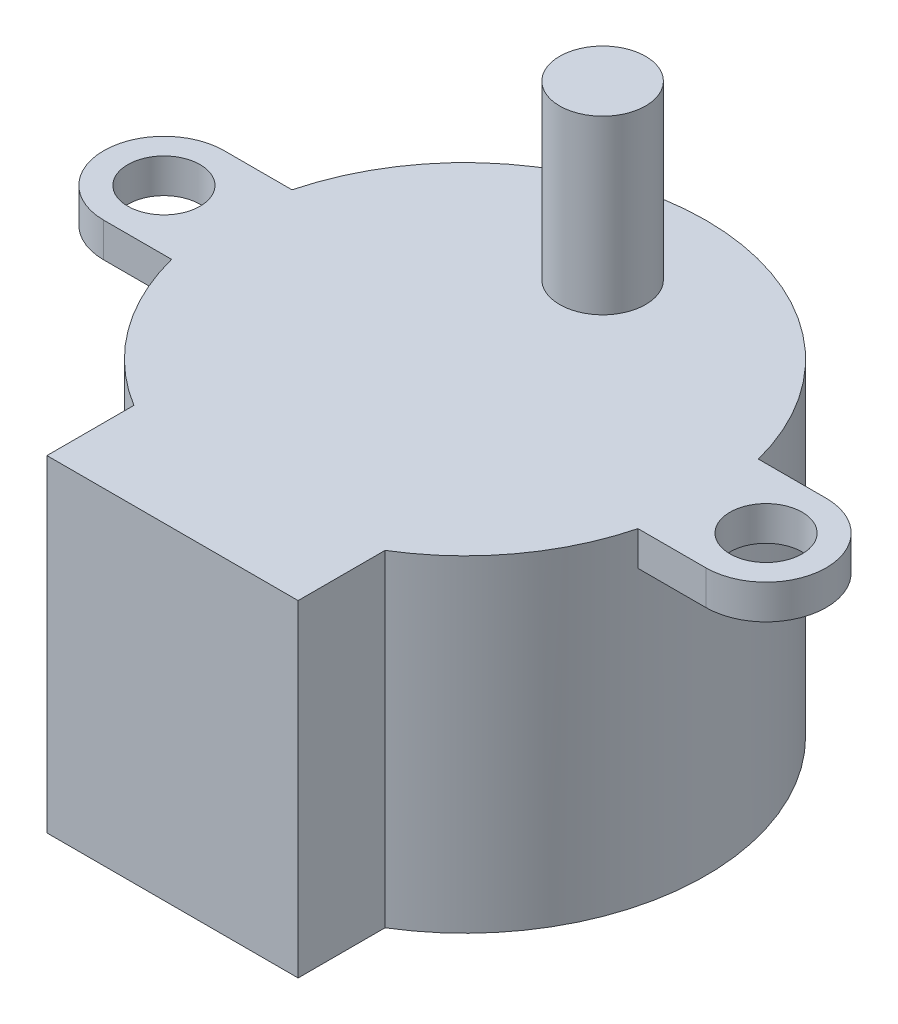
SolidWorks part; units mm, degrees
ref_plane "Спереди" through (0, 0, 0) normal (0, 0, 1) x (1, 0, 0)
ref_plane "Сверху" through (0, 0, 0) normal (0, 1, 0) x (1, 0, 0)
ref_plane "Справа" through (0, 0, 0) normal (1, 0, 0) x (0, 0, -1)
sketch "Sketch1" plane through (0, 0, 0) normal (0, 1, 0) x (1, 0, 0)
  circle A0 centre (0, 0) radius 14
  dimension "D1" = 28
extrude "Boss-Extrude1" add sketch "Sketch1" along normal blind 19
sketch "Sketch2" plane through (0, 19, 0) normal (0, 1, 0) x (1, 0, 0)
  line L0 (-7.3, -17) -> (7.3, -17)
  line L1 (-7.3, -17) -> (-7.3, -11.5042)
  line L2 (-7.3, -11.5042) -> (7.3, -11.5042)
  line L3 (7.3, -11.5042) -> (7.3, -17)
  dimension "D1" = 17
  dimension "D2" = 7.3
  dimension "D3" = 7.3
extrude "Boss-Extrude2" add sketch "Sketch2" against normal blind 19
sketch "Sketch3" plane through (0, 19, 0) normal (0, 1, 0) x (1, 0, 0)
  line L0 (-17.5, 3.5) -> (-12.3999, 3.5)
  line L1 (-12.3999, 3.5) -> (-12.3999, -3.5)
  line L2 (-12.3999, -3.5) -> (-17.5, -3.5)
  line L3 (0, 5.0406) -> (0, -4.2252) construction
  line L4 (12.3999, -3.5) -> (17.5, -3.5)
  line L5 (12.3999, 3.5) -> (12.3999, -3.5)
  line L6 (17.5, 3.5) -> (12.3999, 3.5)
  circle A0 centre (-17.5, 0) radius 2.1
  arc A1 (-17.5, 3.5) -> (-17.5, -3.5) centre (-17.5, 0) ccw
  arc A2 (17.5, 3.5) -> (17.5, -3.5) centre (17.5, 0) cw
  circle A3 centre (17.5, 0) radius 2.1
  dimension "D1" = 4.2
  dimension "D3" = 7
  dimension "D2" = 17.5
extrude "Boss-Extrude3" add sketch "Sketch3" against normal blind 2
sketch "Sketch4" plane through (0, 19, 0) normal (0, 1, 0) x (1, 0, 0)
  circle A0 centre (0, 8) radius 2.5
  dimension "D1" = 5
  dimension "D2" = 8
extrude "Boss-Extrude4" add sketch "Sketch4" along normal blind 10
